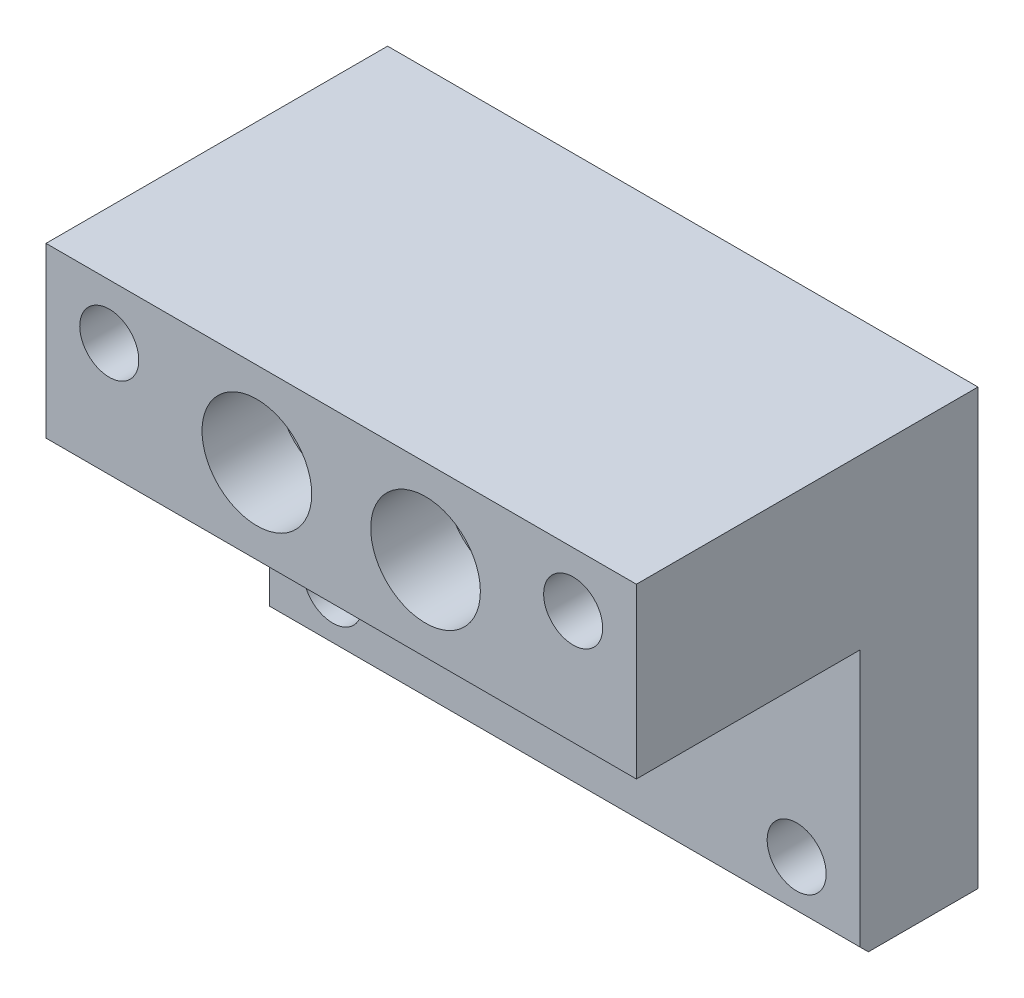
SolidWorks part; units mm, degrees
material "1.4301 (X5CrNi18-10)"
ref_plane "Ebene1" through (0, 0, 0) normal (0, 0, 1) x (1, 0, 0)
ref_plane "Ebene2" through (0, 0, 0) normal (0, 1, 0) x (1, 0, 0)
ref_plane "Ebene3" through (0, 0, 0) normal (1, 0, 0) x (0, 0, -1)
sketch "Skizze1" plane through (0, 0, 0) normal (0, 0, 1) x (1, 0, 0)
  line L0 (0, 72.4291) -> (0, -77.7667) construction
  line L1 (-70, 51.5) -> (70, 51.5)
  line L2 (-70, 51.5) -> (-70, -51.5)
  line L3 (-70, -51.5) -> (70, -51.5)
  line L4 (70, 51.5) -> (70, -51.5)
  line L5 (-94.2698, 0) -> (81.6206, 0) construction
  dimension "D1" = 140
  dimension "D4" = 103
extrude "Basis-Linear austragen" add sketch "Skizze1" along normal mid plane 81
sketch "Skizze8" plane through (-70, 0, 0) normal (-1, 0, 0) x (0, 0, 1)
  line L1 (-12.5, 11.5) -> (40.5, 11.5)
  line L2 (-12.5, 11.5) -> (-12.5, -51.5)
  line L3 (-12.5, -51.5) -> (40.5, -51.5)
  line L4 (40.5, 11.5) -> (40.5, -51.5)
  line L5 (40.5, -51.5) -> (-40.5, -51.5) construction
  line L7 (40.5, 51.5) -> (40.5, -51.5) construction
  dimension "D1" = 53
  dimension "D2" = 63
extrude "Schnitt-Linear austragen1" cut sketch "Skizze8" against normal through all
hole_wizard "Bohrung1" positions "Skizze3" profile "Skizze2" legacy
sketch "Skizze3" plane through (0, 0, 40.5) normal (0, 0, 1) x (1, 0, 0)
  line L0 (-70, 51.5) -> (-70, 11.5) construction
  line L1 (70, 51.5) -> (-70, 51.5) construction
  point P0 (0, -18.5)
  dimension "D1" = 70
  dimension "D2" = 70
sketch "Skizze2" plane through (0, -18.5, 40.5) normal (1, 0, 0) x (0, -1, 0)
  line L0 (0, 0) -> (0, 90)
  line L1 (0, 90) -> (9, 90)
  line L2 (9, 90) -> (9, 18)
  line L3 (9, 18) -> (13, 18)
  line L4 (13, 18) -> (13, 0)
  line L5 (13, 0) -> (0, 0)
  line L6 (0, 110) -> (0, -10) construction
  dimension "Durchmesser" = 18
  dimension "Tiefe" = 90
  dimension "Senkdurchmesser1" = 26
  dimension "Senktiefe1" = 18
hole_wizard "Bohrung2" positions "Skizze5" profile "Skizze4" legacy
sketch "Skizze5" plane through (0, 0, 40.5) normal (0, 0, 1) x (1, 0, 0)
  line L0 (70, 51.5) -> (-70, 51.5) construction
  point P0 (20, 31.5)
  dimension "D1" = 20
  dimension "D2" = 20
sketch "Skizze4" plane through (20, 31.5, 40.5) normal (1, 0, 0) x (0, -1, 0)
  line L0 (0, 0) -> (0, 90)
  line L1 (0, 90) -> (9, 90)
  line L2 (9, 90) -> (9, 18)
  line L3 (9, 18) -> (13, 18)
  line L4 (13, 18) -> (13, 0)
  line L5 (13, 0) -> (0, 0)
  line L6 (0, 110) -> (0, -10) construction
  dimension "Durchmesser" = 18
  dimension "Tiefe" = 90
  dimension "Senkdurchmesser1" = 26
  dimension "Senktiefe1" = 18
pattern_linear "Lineares Muster1" count 2 spacing 40 along (-1, 0, 0) of "Bohrung2"
hole_wizard "Stirnsenkung für M8 Flachkopfschraube mit Schlitz1" positions "Skizze10" profile "Skizze9" counterbore size "M8" standard "DIN" end condition through all
sketch "Skizze10" plane through (0, 0, -40.5) normal (0, 0, -1) x (-1, 0, 0)
  line L1 (70, -51.5) -> (-70, -51.5) construction
  line L2 (-70, 51.5) -> (70, 51.5) construction
  line L3 (-70, -51.5) -> (-70, 51.5) construction
  point P0 (-55, -38.5)
  point P1 (-55, 38.5)
  point P2 (55, 38.5)
  point P3 (55, -38.5)
  dimension "D1" = 13
  dimension "D2" = 13
  dimension "D3" = 15
  dimension "D4" = 110
sketch "Skizze9" plane through (55, -38.5, -40.5) normal (1, 0, 0) x (0, 1, 0)
  line L0 (0, 0) -> (0, 81)
  line L1 (0, 81) -> (7, 81)
  line L3 (7, 81) -> (7, 13)
  line L4 (7, 13) -> (10, 13)
  line L5 (10, 13) -> (10, 0)
  line L7 (10, 0) -> (0, 0)
  line L11 (0, -6.35) -> (0, 107.95) construction
  dimension "Bohrerdurchmesser" = 14
  dimension "Bohrungstiefe" = 81
  dimension "Senkdurchmesser2" = 20
  dimension "Senktiefe2" = 13
sketch "Skizze11" plane through (0, 0, -12.5) normal (0, 0, 1) x (1, 0, 0)
  circle A0 centre (0, -18.5) radius 13
  circle A1 centre (0, -18.5) radius 9 construction
  dimension "D1" = 26
extrude "Schnitt-Linear austragen2" cut sketch "Skizze11" against normal blind 18
chamfer "Fase1" distance 2 angle 45 1 edges at (0, -51.5, -12.5)
